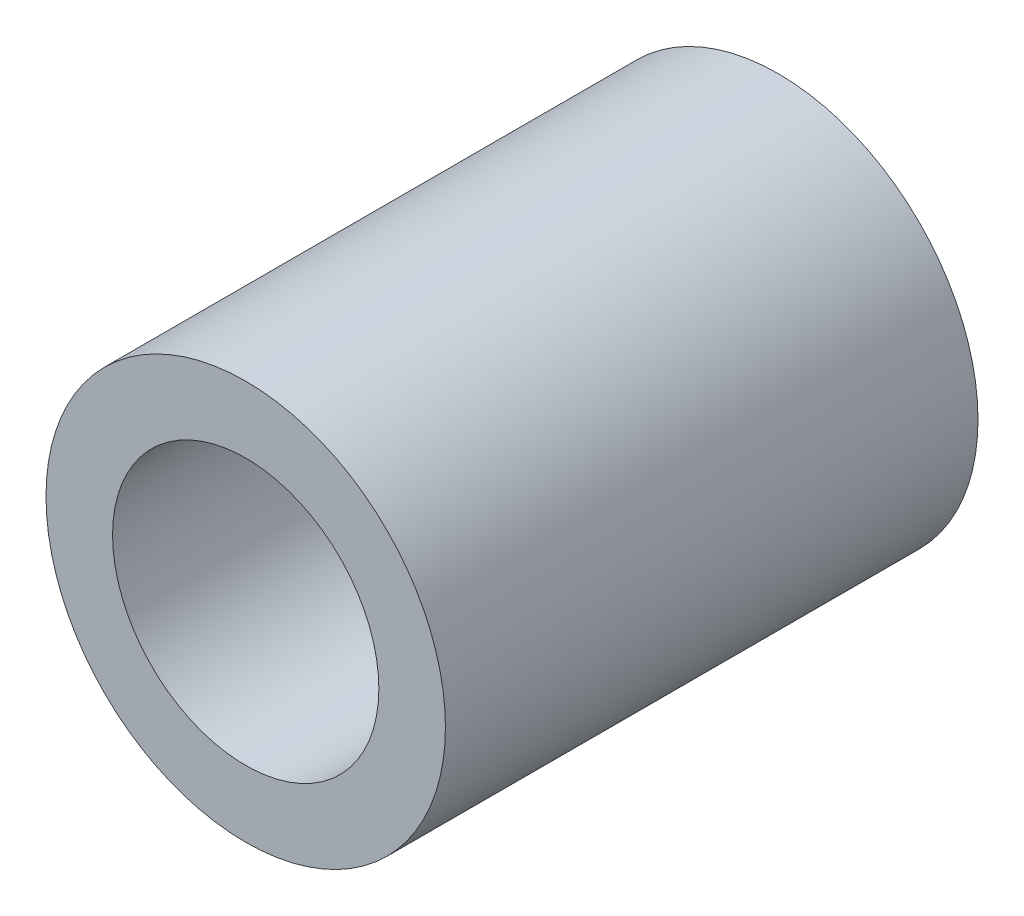
SolidWorks part; units mm, degrees
ref_plane "Front Plane" through (0, 0, 0) normal (0, 0, 1) x (1, 0, 0)
ref_plane "Top Plane" through (0, 0, 0) normal (0, 1, 0) x (1, 0, 0)
ref_plane "Right Plane" through (0, 0, 0) normal (1, 0, 0) x (0, 0, -1)
sketch "Sketch1" plane through (0, 0, 0) normal (0, 0, 1) x (1, 0, 0)
  circle A0 centre (0, 0) radius 9.525
  circle A1 centre (0, 0) radius 6.35
  dimension "OD" = 19.05
  dimension "ID" = 12.7
extrude "Extrude1" add sketch "Sketch1" along normal mid plane 25.4
sketch "Sketch2" plane through (0, 0, 0) normal (1, 0, 0) x (0, 0, -1)
  line L0 (-12.7, -6.35) -> (12.7, -6.35) construction
  line L3 (12.7, 6.35) -> (-12.7, 6.35) construction
  line L5 (-12.7, -6.35) -> (12.7, -6.35)
  line L6 (12.7, 6.35) -> (-12.7, 6.35)
sketch "Sketch4" plane through (0, 0, 12.7) normal (0, 0, 1) x (1, 0, 0)
  line L0 (0, 0) -> (-4.4901, 4.4901)
  line L1 (0, -6.985) -> (0, 6.985) construction
  circle A0 centre (0, 0) radius 6.35 construction
  dimension "D1" = 45
